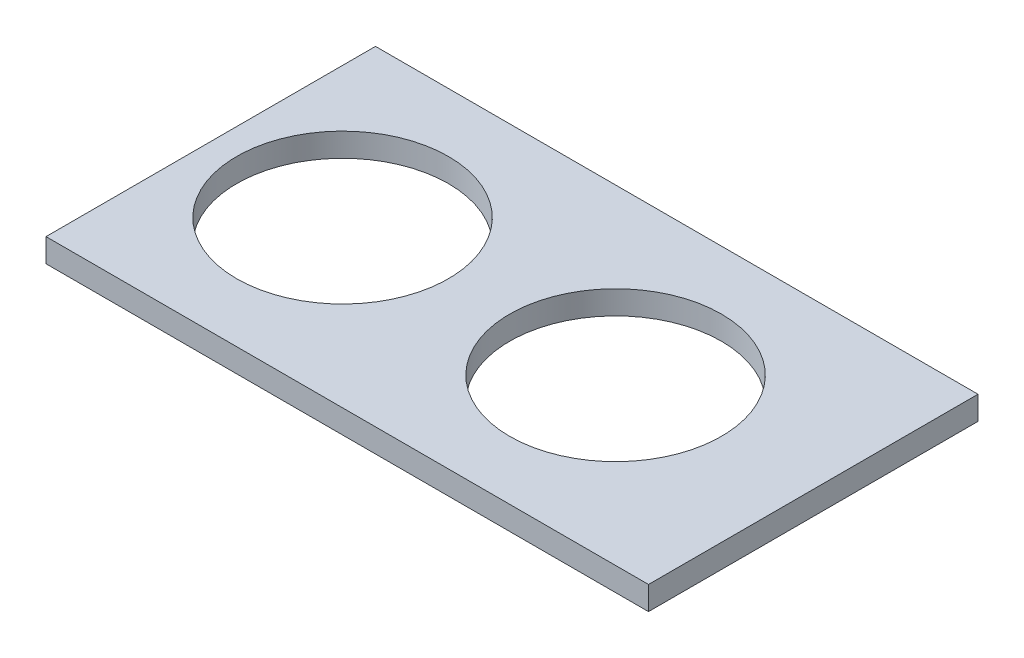
SolidWorks part; units mm, degrees
ref_plane "Front Plane" through (0, 0, 0) normal (0, 0, 1) x (1, 0, 0)
ref_plane "Top Plane" through (0, 0, 0) normal (0, 1, 0) x (1, 0, 0)
ref_plane "Right Plane" through (0, 0, 0) normal (1, 0, 0) x (0, 0, -1)
sketch "Sketch1" plane through (0, 0, 0) normal (0, 1, 0) x (1, 0, 0)
  line L1 (-17.78, -22.225) -> (63.5, -22.225)
  line L2 (-17.78, -22.225) -> (-17.78, 22.225)
  line L3 (-17.78, 22.225) -> (63.5, 22.225)
  line L4 (63.5, -22.225) -> (63.5, 22.225)
  line L5 (-17.78, -22.225) -> (63.5, 22.225) construction
  line L6 (-17.78, 22.225) -> (63.5, -22.225) construction
  circle A0 centre (0, 0) radius 11.43 construction
  circle A2 centre (36.83, 0) radius 25.4 construction
  circle A3 centre (0, 0) radius 14.2875
  circle A4 centre (36.83, 0) radius 14.2875
  point P4 (22.86, 0)
  point P13 (0, 0)
  dimension "D1" = 22.86
  dimension "D2" = 50.8
  dimension "D3" = 6.35
  dimension "D5" = 28.575
  dimension "D4" = 63.5
  dimension "D6" = 44.45
extrude "Boss-Extrude1" add sketch "Sketch1" along normal blind 3.175 contours L1 L4 L3 L2 A4 A3
